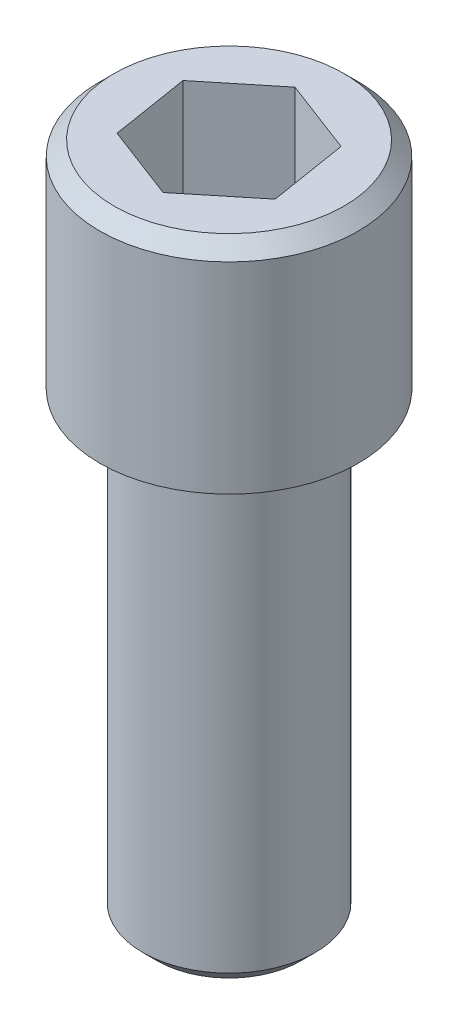
SolidWorks part; units mm, degrees
ref_plane "Přední rovina" through (0, 0, 0) normal (0, 0, 1) x (1, 0, 0)
ref_plane "Horní rovina" through (0, 0, 0) normal (0, 1, 0) x (1, 0, 0)
ref_plane "Pravá rovina" through (0, 0, 0) normal (1, 0, 0) x (0, 0, -1)
sketch "Skica1" plane through (0, 0, 0) normal (0, 1, 0) x (1, 0, 0)
  circle A0 centre (0, 0) radius 1.5
  dimension "D1" = 3
extrude "Přidat vysunutím1" add sketch "Skica1" along normal blind 8
sketch "Skica2" plane through (0, 8, 0) normal (0, 1, 0) x (1, 0, 0)
  circle A0 centre (0, 0) radius 2.25
  dimension "D1" = 4.5
extrude "Přidat vysunutím2" add sketch "Skica2" along normal blind 3.75
sketch "Skica3" plane through (0, 11.75, 0) normal (0, 1, 0) x (1, 0, 0)
  line L1 (-1.0744, -0.875) -> (0.2206, -1.368)
  line L2 (0.2206, -1.368) -> (1.295, -0.493)
  line L3 (1.295, -0.493) -> (1.0744, 0.875)
  line L4 (1.0744, 0.875) -> (-0.2206, 1.368)
  line L5 (-0.2206, 1.368) -> (-1.295, 0.493)
  line L6 (-1.295, 0.493) -> (-1.0744, -0.875)
  circle A0 centre (0, 0) radius 1.2 construction
  dimension "D1" = 2.4
extrude "Odebrat vysunutím1" cut sketch "Skica3" against normal blind 2.25
chamfer "Zkosení1" distance 0.25 angle 45 1 edges at (0, 11.75, 2.25)
chamfer "Zkosení2" distance 0.25 angle 45 1 edges at (0, 0, 1.5)
